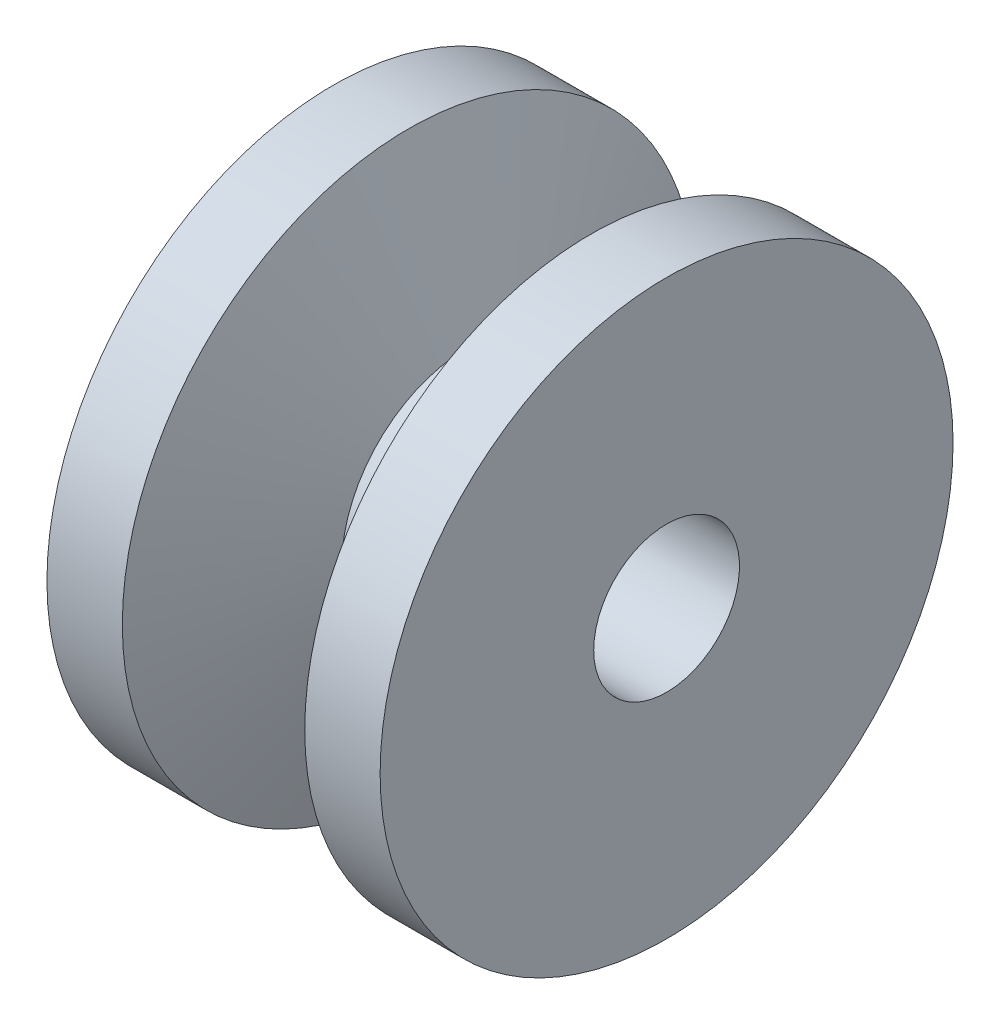
SolidWorks part; units mm, degrees
ref_plane "Front Plane" through (0, 0, 0) normal (0, 0, 1) x (1, 0, 0)
ref_plane "Top Plane" through (0, 0, 0) normal (0, 1, 0) x (1, 0, 0)
ref_plane "Right Plane" through (0, 0, 0) normal (1, 0, 0) x (0, 0, -1)
sketch "Sketch1" plane through (0, 0, 0) normal (0, 1, 0) x (1, 0, 0)
  line L1 (0, 14.478) -> (3.81, 14.478)
  line L2 (3.81, 14.478) -> (6.7684, 6.35)
  line L3 (6.7684, 6.35) -> (10.0704, 6.35)
  line L4 (10.0704, 6.35) -> (13.0287, 14.478)
  line L5 (13.0287, 14.478) -> (16.8387, 14.478)
  line L6 (16.8387, 14.478) -> (16.8387, 3.683)
  line L8 (0, 14.478) -> (0, 3.683)
  line L9 (0, 3.683) -> (16.8387, 3.683)
  dimension "D1" = 3.683
  dimension "D2" = 14.478
  dimension "D3" = 3.302
  dimension "D4" = 3.81
  dimension "D5" = 6.35
  dimension "D6" = 3.81
  dimension "D7" = 110
  dimension "D8" = 110
ref_axis "Axis1" through (0, 0, 0) along (1, 0, 0)
revolve "Revolve1" add sketch "Sketch1" angle 360 about axis through (0, 0, 0) along (1, 0, 0)
